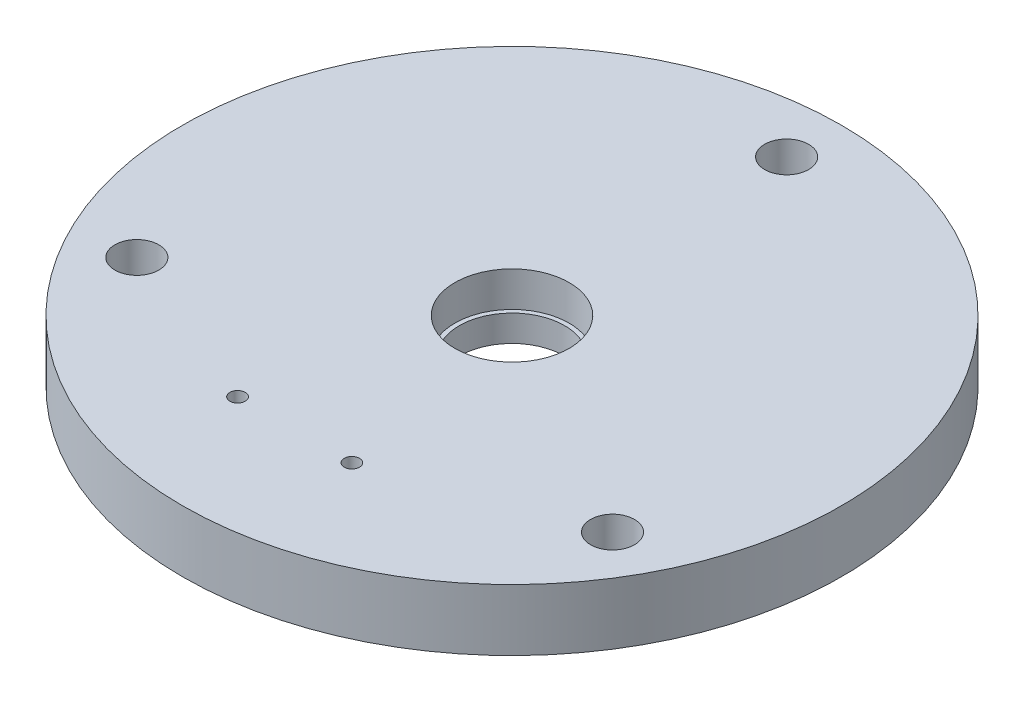
SolidWorks part; units mm, degrees
ref_plane "Front Plane" through (0, 0, 0) normal (0, 0, 1) x (1, 0, 0)
ref_plane "Top Plane" through (0, 0, 0) normal (0, 1, 0) x (1, 0, 0)
ref_plane "Right Plane" through (0, 0, 0) normal (1, 0, 0) x (0, 0, -1)
sketch "Sketch1" plane through (0, 0, 0) normal (0, 1, 0) x (1, 0, 0)
  circle A0 centre (0, 0) radius 75
  dimension "D1" = 150
extrude "Boss-Extrude1" add sketch "Sketch1" along normal blind 14
sketch "Sketch2" plane through (0, 14, 0) normal (0, 1, 0) x (1, 0, 0)
  circle A0 centre (0, 0) radius 13
  dimension "D1" = 26
extrude "Cut-Extrude1" cut sketch "Sketch2" against normal blind 8
sketch "Sketch3" plane through (0, 6, 0) normal (0, 1, 0) x (1, 0, 0)
  circle A0 centre (0, 0) radius 12
  dimension "D1" = 24
extrude "Cut-Extrude2" cut sketch "Sketch3" against normal blind 8
sketch "Sketch4" plane through (0, 14, 0) normal (0, 1, 0) x (1, 0, 0)
  line L0 (0, 0) -> (0, 62.5) construction
  line L1 (0, 0) -> (54.1266, -31.25) construction
  line L2 (0, 0) -> (-54.1266, -31.25) construction
  circle A0 centre (0, 62.5) radius 5
  circle A1 centre (-54.1266, -31.25) radius 5
  circle A2 centre (54.1266, -31.25) radius 5
  circle A3 centre (0, 0) radius 62.5
  dimension "D1" = 10
  dimension "D2" = 10
  dimension "D3" = 10
  dimension "D4" = 62.5
  dimension "D5" = 120
extrude "Cut-Extrude4" cut sketch "Sketch4" against normal through all contours A3 A0 | A0 A3 | A2 A3 | A3 A2 | A3 A1 | A1 A3
cosmetic thread "Cosmetic Thread3" parameters "D2"=11
cosmetic thread "Cosmetic Thread4" parameters "D2"=11
cosmetic thread "Cosmetic Thread5" parameters "D2"=11
sketch "Sketch5" plane through (0, 14, 0) normal (0, 1, 0) x (1, 0, 0)
  line L0 (-33.2016, -67.2507) -> (-33.2016, -57.2507)
  line L1 (-33.2016, -57.2507) -> (28.7984, -57.2507)
  line L2 (-33.2016, -57.2507) -> (-33.2016, -22.2507)
  line L3 (-33.2016, -22.2507) -> (28.7984, -22.2507)
  line L4 (28.7984, -57.2507) -> (28.7984, -22.2507)
  line L5 (28.7984, -57.2507) -> (28.7984, -69.2507)
  circle A0 centre (0, 0) radius 75 construction
  circle A1 centre (-15.2016, -47.2507) radius 1.75
  circle A2 centre (10.7984, -47.2507) radius 1.75
  dimension "D9" = 3.5
  dimension "D10" = 3.5
  dimension "D1" = 35
  dimension "D2" = 62
  dimension "D3" = 10
  dimension "D4" = 12
  dimension "D5" = 10
  dimension "D6" = 10
  dimension "D7" = 18
  dimension "D8" = 18
extrude "Cut-Extrude5" cut sketch "Sketch5" against normal through all contours A1 | A2
cosmetic thread "Cosmetic Thread1" parameters "D2"=4
cosmetic thread "Cosmetic Thread2" parameters "D2"=4
